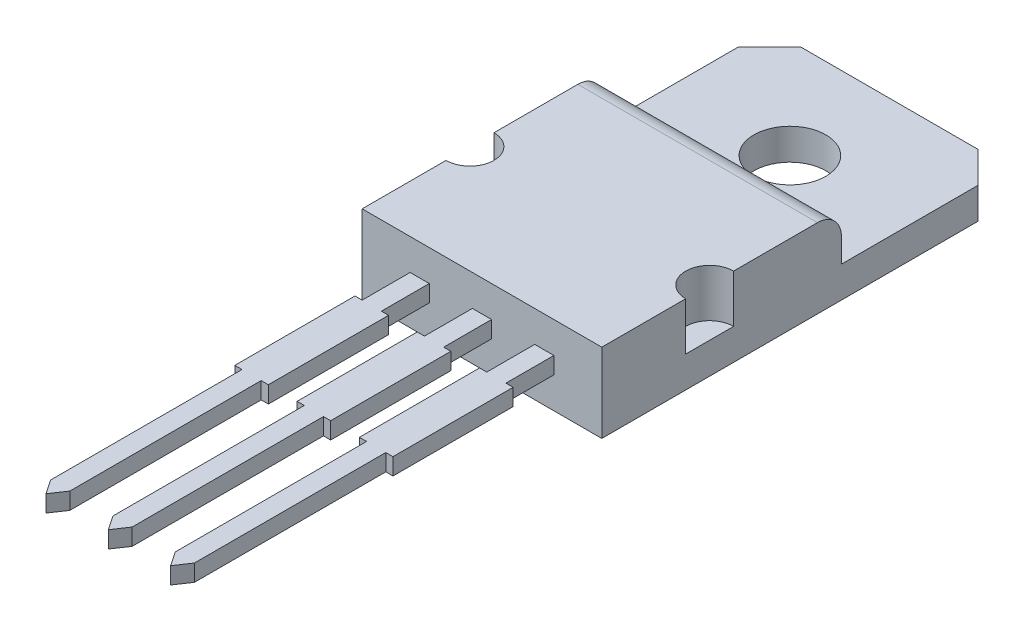
SolidWorks part; units mm, degrees
ref_plane "Front Plane" through (0, 0, 0) normal (0, 0, 1) x (1, 0, 0)
ref_plane "Top Plane" through (0, 0, 0) normal (0, 1, 0) x (1, 0, 0)
ref_plane "Right Plane" through (0, 0, 0) normal (1, 0, 0) x (0, 0, -1)
sketch "Sketch1" plane through (0, 0, 0) normal (0, 1, 0) x (1, 0, 0)
  line L0 (0, 0) -> (0.4, -0.5945)
  line L2 (0, 0) -> (0, 7.985)
  line L3 (0, 15) -> (0.8, 15)
  line L4 (0.8, 0) -> (0.8, 7.985)
  line L5 (0.4, -0.5945) -> (0.8, 0)
  line L6 (0.4, 15.9552) -> (0.4, -1.7303) construction
  line L7 (0.8, 13) -> (1.1, 13)
  line L8 (-0.3, 7.985) -> (0, 7.985)
  line L9 (-0.3, 7.985) -> (-0.3, 13)
  line L10 (-0.3, 13) -> (0, 13)
  line L11 (1.1, 7.985) -> (1.1, 13)
  line L12 (0, 13) -> (0, 15)
  line L13 (0.8, 13) -> (0.8, 15)
  line L14 (0.8, 7.985) -> (1.1, 7.985)
  line L15 (-0.9, 15.6449) -> (-0.9, 0) construction
  line L16 (-2.2, 15.9552) -> (-2.2, -1.7303) construction
  line L17 (-2.6, 7.985) -> (-2.9, 7.985)
  line L18 (-2.6, 13) -> (-2.6, 15)
  line L19 (-1.8, 13) -> (-1.8, 15)
  line L20 (-2.9, 7.985) -> (-2.9, 13)
  line L21 (-1.5, 13) -> (-1.8, 13)
  line L22 (-1.5, 7.985) -> (-1.5, 13)
  line L23 (-1.5, 7.985) -> (-1.8, 7.985)
  line L24 (-2.6, 13) -> (-2.9, 13)
  line L25 (-2.2, -0.5945) -> (-2.6, 0)
  line L26 (-2.6, 0) -> (-2.6, 7.985)
  line L27 (-1.8, 15) -> (-2.6, 15)
  line L28 (-1.8, 0) -> (-1.8, 7.985)
  line L29 (-1.8, 0) -> (-2.2, -0.5945)
  line L30 (-3.5, 15.9552) -> (-3.5, -1.7303) construction
  line L31 (-5.2, 0) -> (-4.8, -0.5945)
  line L32 (-5.2, 0) -> (-5.2, 7.985)
  line L33 (-5.2, 15) -> (-4.4, 15)
  line L34 (-4.4, 0) -> (-4.4, 7.985)
  line L35 (-4.8, -0.5945) -> (-4.4, 0)
  line L36 (-4.4, 13) -> (-4.1, 13)
  line L37 (-5.5, 7.985) -> (-5.2, 7.985)
  line L38 (-5.5, 7.985) -> (-5.5, 13)
  line L39 (-5.5, 13) -> (-5.2, 13)
  line L40 (-4.1, 7.985) -> (-4.1, 13)
  line L41 (-5.2, 13) -> (-5.2, 15)
  line L42 (-4.4, 13) -> (-4.4, 15)
  line L43 (-4.4, 7.985) -> (-4.1, 7.985)
  point P14 (0.4, 15)
  dimension "D1" = 15
  dimension "D2" = 0.8
  dimension "D3" = 0.7165
  dimension "D4" = 0.6
  dimension "D5" = 1.4
  dimension "D6" = 2
  dimension "D7" = 0.6
extrude "Boss-Extrude1" add sketch "Sketch1" along normal blind 0.7
sketch "Sketch6" plane through (0, 0, 0) normal (0, 1, 0) x (1, 0, 0)
  line L0 (-4.4, 15) -> (-5.2, 15) construction
  line L1 (-7.2, 15) -> (2.8, 15)
  line L2 (-7.2, 15) -> (-7.2, 25)
  line L3 (-7.2, 25) -> (2.8, 25)
  line L4 (2.8, 15) -> (2.8, 25)
  line L5 (-2.2, -0.5945) -> (-2.2, 27.9092) construction
  dimension "D1" = 10
  dimension "D2" = 10
extrude "Boss-Extrude2" add sketch "Sketch6" along normal blind 2
fillet "Fillet1" radius 1 1 edges at (-2.2, 2, -25)
sketch "Sketch7" plane through (0, 2, 0) normal (0, 1, 0) x (1, 0, 0)
  line L0 (-7.2, 19.5) -> (2.8, 19.5) construction
  line L1 (-7.2, 24) -> (-7.2, 15) construction
  line L2 (2.8, 15) -> (2.8, 24) construction
  line L3 (-7.2, 15) -> (2.8, 15) construction
  circle A0 centre (-7.2, 19.5) radius 1
  circle A1 centre (2.8, 19.5) radius 1
  dimension "D2" = 2
  dimension "D3" = 2
  dimension "D1" = 4.5
extrude "Cut-Extrude2" cut sketch "Sketch7" against normal blind 2
sketch "Sketch8" plane through (0, 0, 0) normal (0, -1, 0) x (1, 0, 0)
  line L0 (-7.2, -18.5) -> (-7.2, -15) construction
  line L1 (-7.2, -15) -> (2.8, -15)
  line L2 (-7.2, -15) -> (-7.2, -30.7)
  line L3 (-5.9, -32) -> (1.5, -32)
  line L4 (2.8, -15) -> (2.8, -30.7)
  line L5 (2.8, -15) -> (2.8, -18.5) construction
  line L6 (-1.8, -15) -> (0, -15) construction
  line L7 (-7.2, -30.7) -> (-5.9, -32)
  line L8 (1.5, -32) -> (2.8, -30.7)
  point P1 (2.8, -32)
  point P2 (-7.2, -32)
  dimension "D1" = 17
extrude "Boss-Extrude3" add sketch "Sketch8" along normal blind 1.3
sketch "Sketch9" plane through (0, 0, 0) normal (0, 1, 0) x (1, 0, 0)
  circle A0 centre (-2.2, 27.85) radius 1.5
  dimension "D1" = 3
extrude "Cut-Extrude3" cut sketch "Sketch9" against normal blind 1.3 contours A0
